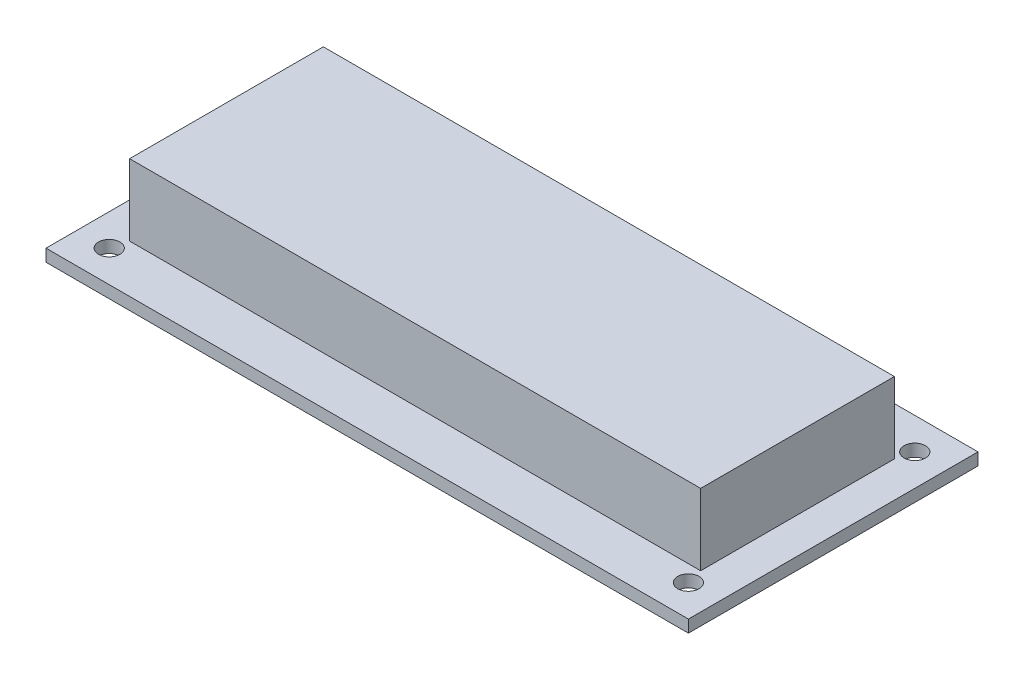
SolidWorks part; units mm, degrees
ref_plane "Front Plane" through (0, 0, 0) normal (0, 0, 1) x (1, 0, 0)
ref_plane "Top Plane" through (0, 0, 0) normal (0, 1, 0) x (1, 0, 0)
ref_plane "Right Plane" through (0, 0, 0) normal (1, 0, 0) x (0, 0, -1)
sketch "Sketch1" plane through (0, 0, 0) normal (0, 1, 0) x (1, 0, 0)
  line L1 (-40.005, 18.034) -> (40.005, 18.034)
  line L2 (-40.005, 18.034) -> (-40.005, -18.034)
  line L3 (-40.005, -18.034) -> (40.005, -18.034)
  line L4 (40.005, 18.034) -> (40.005, -18.034)
  line L5 (-40.005, 18.034) -> (40.005, -18.034) construction
  line L6 (-40.005, -18.034) -> (40.005, 18.034) construction
  point P0 (0, 0)
  dimension "D1" = 80.01
  dimension "D2" = 36.068
extrude "Boss-Extrude1" add sketch "Sketch1" along normal blind 1.524
sketch "Sketch2" plane through (0, 1.524, 0) normal (0, 1, 0) x (1, 0, 0)
  line L0 (-40.005, 18.034) -> (-40.005, -18.034) construction
  line L1 (40.005, 18.034) -> (-40.005, 18.034) construction
  line L2 (-36.068, 14.097) -> (-36.068, -14.097) construction
  line L3 (-36.068, 14.097) -> (36.068, 14.097) construction
  line L4 (36.068, 14.097) -> (36.068, -14.097) construction
  line L5 (36.068, -14.097) -> (-36.068, -14.097) construction
  line L6 (40.005, -18.034) -> (40.005, 18.034) construction
  line L7 (-40.005, -18.034) -> (40.005, -18.034) construction
  circle A0 centre (-36.068, 14.097) radius 1.3335
  circle A1 centre (36.068, 14.097) radius 1.3335
  circle A2 centre (36.068, -14.097) radius 1.3335
  circle A3 centre (-36.068, -14.097) radius 1.3335
  dimension "D1" = 2.667
  dimension "D2" = 2.667
  dimension "D3" = 2.667
  dimension "D4" = 2.667
  dimension "D5" = 3.937
  dimension "D7" = 3.937
  dimension "D8" = 3.937
  dimension "D6" = 3.937
extrude "Cut-Extrude1" cut sketch "Sketch2" against normal up to next
sketch "Sketch3" plane through (0, 1.524, 0) normal (0, 1, 0) x (1, 0, 0)
  line L1 (-35.56, 12.065) -> (35.56, 12.065)
  line L2 (-35.56, 12.065) -> (-35.56, -12.065)
  line L3 (-35.56, -12.065) -> (35.56, -12.065)
  line L4 (35.56, 12.065) -> (35.56, -12.065)
  line L5 (-35.56, 12.065) -> (35.56, -12.065) construction
  line L6 (-35.56, -12.065) -> (35.56, 12.065) construction
  point P0 (0, 0)
  dimension "D1" = 24.13
  dimension "D2" = 71.12
extrude "Boss-Extrude2" add sketch "Sketch3" along normal blind 8.89
sketch "Sketch4" plane through (0, 1.524, 0) normal (0, 1, 0) x (1, 0, 0)
  line L0 (-35.56, 12.065) -> (-35.56, -12.065) construction
  line L1 (-35.56, 9.0678) -> (-38.481, 9.0678)
  line L2 (-35.56, 9.0678) -> (-35.56, -9.017)
  line L3 (-35.56, -9.017) -> (-38.481, -9.017)
  line L4 (-38.481, 9.0678) -> (-38.481, -9.017)
  line L5 (-35.56, -12.065) -> (35.56, -12.065) construction
  dimension "D1" = 18.0848
  dimension "D2" = 2.921
  dimension "D3" = 3.048
extrude "Boss-Extrude3" add sketch "Sketch4" along normal blind 3.175
